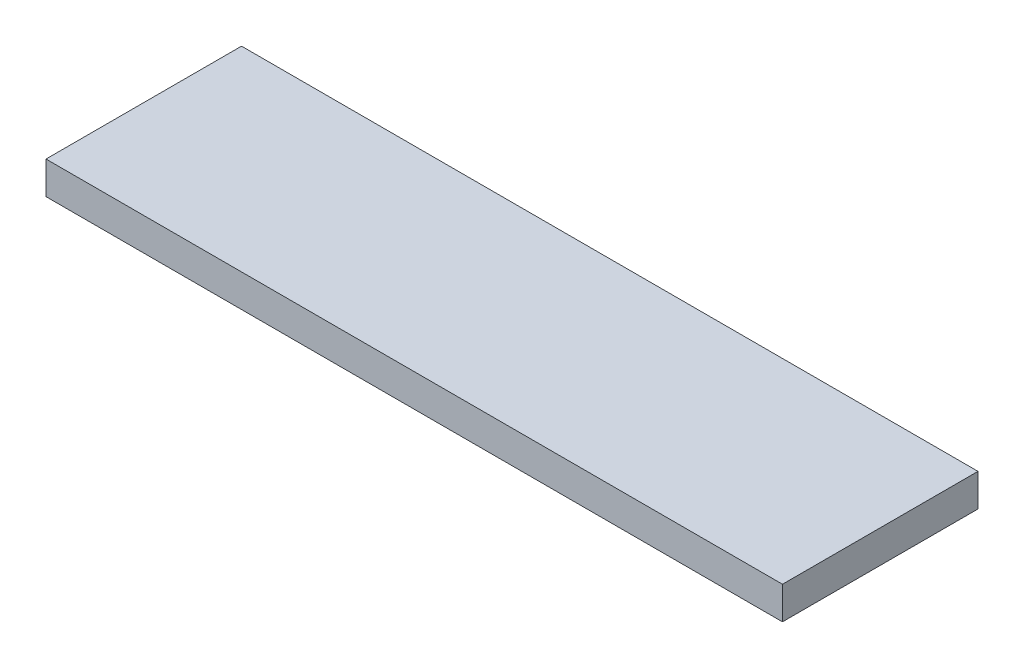
SolidWorks part; units mm, degrees
ref_plane "Front Plane" through (0, 0, 0) normal (0, 0, 1) x (1, 0, 0)
ref_plane "Top Plane" through (0, 0, 0) normal (0, 1, 0) x (1, 0, 0)
ref_plane "Right Plane" through (0, 0, 0) normal (1, 0, 0) x (0, 0, -1)
sketch "Sketch1" plane through (0, 0, 0) normal (0, 1, 0) x (1, 0, 0)
  line L1 (-113, -30) -> (113, -30)
  line L2 (-113, -30) -> (-113, 30)
  line L3 (-113, 30) -> (113, 30)
  line L4 (113, -30) -> (113, 30)
  line L5 (-113, -30) -> (113, 30) construction
  line L6 (-113, 30) -> (113, -30) construction
  point P0 (0, 0)
  dimension "D1" = 226
  dimension "D2" = 60
extrude "Boss-Extrude1" add sketch "Sketch1" along normal blind 10
